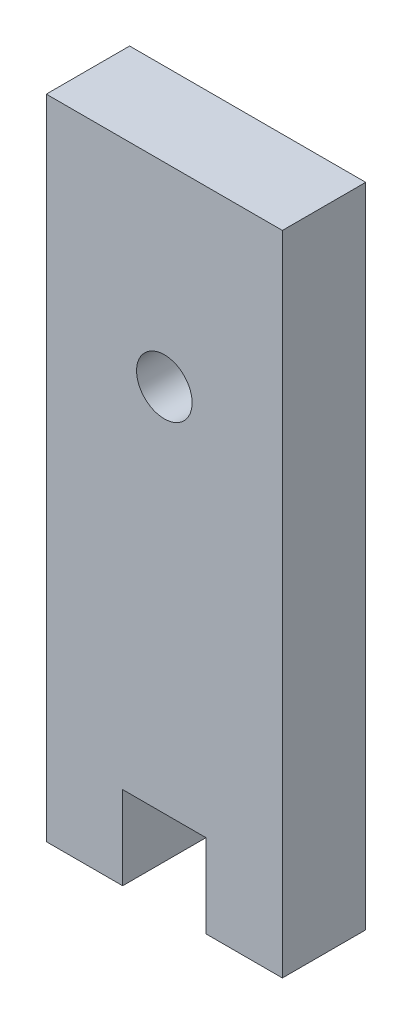
SolidWorks part; units mm, degrees
ref_plane "Front Plane" through (0, 0, 0) normal (0, 0, 1) x (1, 0, 0)
ref_plane "Top Plane" through (0, 0, 0) normal (0, 1, 0) x (1, 0, 0)
ref_plane "Right Plane" through (0, 0, 0) normal (1, 0, 0) x (0, 0, -1)
sketch "Sketch2" plane through (0, 0, 0) normal (0, 0, 1) x (1, 0, 0)
  line L0 (1.8214, 13.0563) -> (1.8214, -7.439) construction
  line L1 (-2.4286, -7.4437) -> (-2.4286, 13.0563)
  line L2 (-2.4286, 13.0563) -> (6.0714, 13.0563)
  line L3 (6.0714, -7.2528) -> (6.0714, 13.0563)
  line L4 (-2.4286, -7.4437) -> (6.0714, 13.0563) construction
  line L5 (-2.4286, 13.0563) -> (6.0714, -7.2528) construction
  line L14 (-2.4286, -7.4437) -> (-2.4286, -10.2528)
  line L15 (-2.4286, -10.2528) -> (0.3214, -10.2528)
  line L16 (6.0714, -7.2528) -> (6.0714, -10.2528)
  line L17 (0.3214, -10.2528) -> (0.3214, -7.2528)
  line L18 (0.3214, -7.2528) -> (3.3214, -7.2528)
  line L19 (3.3214, -10.2528) -> (3.3214, -7.2528)
  line L21 (3.3214, -10.2528) -> (6.0714, -10.2528)
  circle A0 centre (1.8214, 6.0563) radius 1
  point P0 (1.8413, 2.8543)
  dimension "D3" = 2
  dimension "D1" = 20.5
  dimension "D2" = 1.5
  dimension "D4" = 3
  dimension "D5" = 3
  dimension "D6" = 3
  dimension "D7" = 8.5
  dimension "D8" = 0
  dimension "D9" = 7
extrude "Boss-Extrude1" add sketch "Sketch2" along normal blind 3
